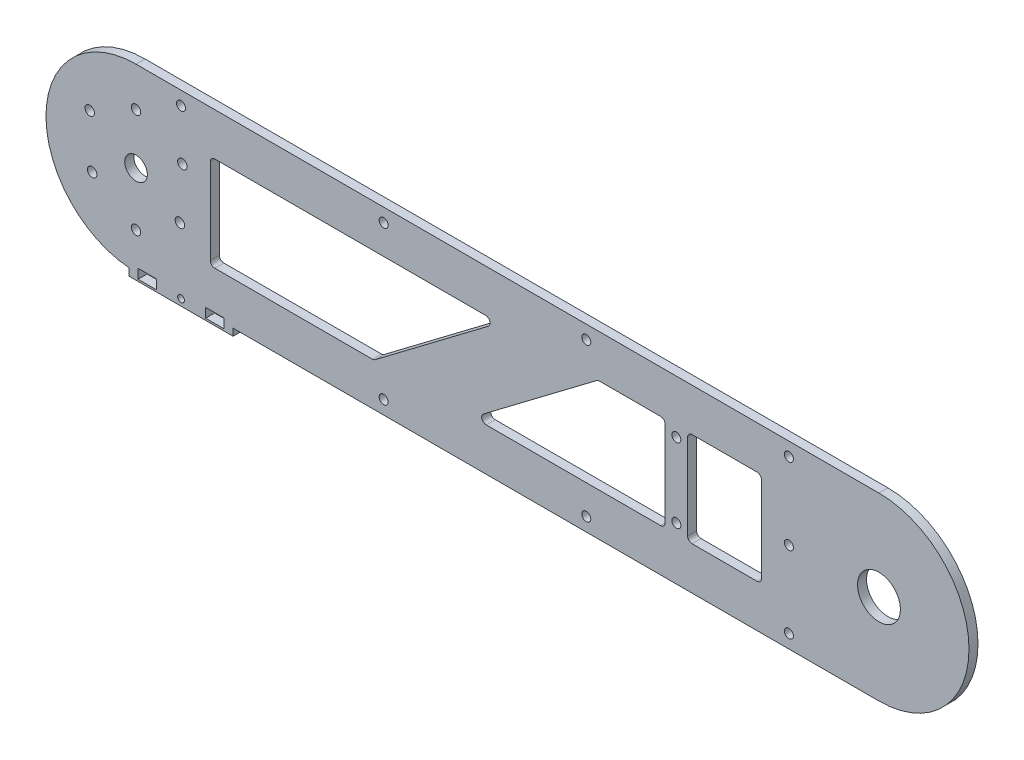
SolidWorks part; units mm, degrees
ref_plane "前视基准面" through (0, 0, 0) normal (0, 0, 1) x (1, 0, 0)
ref_plane "上视基准面" through (0, 0, 0) normal (0, 1, 0) x (1, 0, 0)
ref_plane "右视基准面" through (0, 0, 0) normal (1, 0, 0) x (0, 0, -1)
sketch "草图1" plane through (0, 0, 0) normal (0, 0, 1) x (1, 0, 0)
  line L0 (-1.4571, -0.1457) -> (37.8152, -22.8196) construction
  line L1 (-1.4571, -0.1457) -> (328.5429, -0.1457) construction
  line L3 (-1.4571, -40.1457) -> (328.5429, -40.1457)
  line L8 (-1.4571, 39.8543) -> (328.5429, 39.8543)
  circle A0 centre (-1.4571, -0.1457) radius 23.75 construction
  circle A1 centre (-1.4571, -0.1457) radius 22.5 construction
  circle A2 centre (-1.4571, -23.8957) radius 2.1
  circle A3 centre (18.0284, -11.3957) radius 2.1
  circle A4 centre (-1.4571, -0.1457) radius 40 construction
  circle A6 centre (-1.4571, -0.1457) radius 5.02
  circle A12 centre (328.5429, -0.1457) radius 40 construction
  arc A16 (-1.4571, -40.1457) -> (-1.4571, 39.8543) centre (-1.4571, -0.1457) cw
  arc A21 (328.5429, -40.1457) -> (328.5429, 39.8543) centre (328.5429, -0.1457) ccw
  circle A22 centre (328.5429, -0.1457) radius 9.52
  circle A23 centre (288.5429, -0.1457) radius 2
  circle A24 centre (238.5429, 16.3543) radius 2
  circle A25 centre (238.5429, -16.6457) radius 2
  circle A26 centre (-20.9427, -11.3957) radius 2.1
  circle A27 centre (-22.0252, 11.7293) radius 2.1
  circle A28 centre (-1.4571, 22.3543) radius 2.1
  circle A29 centre (19.111, 11.7293) radius 2.1
  dimension "D1" = 45
  dimension "D2" = 3
  dimension "D3" = 4.2
  dimension "D4" = 19.04
  dimension "D5" = 80
  dimension "D6" = 80
  dimension "D7" = 10.04
  dimension "D11" = 4
  dimension "D12" = 47.5
  dimension "D8" = 330
  dimension "D9" = 50
  dimension "D10" = 16.5
extrude "凸台-拉伸1" add sketch "草图1" along normal blind 4 contours L3
sketch "草图3" plane through (0, 0, 4) normal (0, 0, 1) x (1, 0, 0)
  line L1 (41.6429, -39.4527) -> (-4.5571, -39.4527)
  line L2 (41.6429, -39.4527) -> (41.6429, -43.2699)
  line L3 (41.6429, -43.2699) -> (-4.5571, -43.2699)
  line L4 (-4.5571, -39.4527) -> (-4.5571, -43.2699)
  line L7 (-1.4571, -40.1457) -> (328.5429, -40.1457) construction
  dimension "D1" = 3.1
  dimension "D2" = 46.2
  dimension "D3" = 3.1242
extrude "凸台-拉伸2" add sketch "草图3" against normal blind 4
sketch "草图2" plane through (0, 0, 4) normal (0, 0, 1) x (1, 0, 0)
  line L0 (18.5429, 33.8543) -> (198.5429, 33.8543) construction
  line L1 (108.5429, -34.1457) -> (198.5429, 33.8543) construction
  line L2 (18.5429, 33.8543) -> (18.5429, -34.1457) construction
  line L3 (18.5429, -34.1457) -> (108.5429, -34.1457) construction
  line L4 (31.5429, -21.1457) -> (104.1839, -21.1457)
  line L5 (104.1839, -21.1457) -> (159.7721, 20.8543)
  line L6 (31.5429, 20.8543) -> (159.7721, 20.8543)
  line L7 (31.5429, 20.8543) -> (31.5429, -21.1457)
  line L8 (108.5429, -34.1457) -> (288.5429, -34.1457) construction
  line L9 (288.5429, -34.1457) -> (288.5429, 33.8543) construction
  line L10 (288.5429, 33.8543) -> (198.5429, 33.8543) construction
  line L11 (276.3527, 20.8543) -> (203.7117, 20.8543) construction
  line L12 (148.1234, -21.1457) -> (203.7117, 20.8543)
  line L13 (148.1234, -21.1457) -> (276.3527, -21.1457) construction
  line L14 (276.3527, -21.1457) -> (276.3527, 20.8543)
  line L15 (233.5429, 20.8543) -> (233.5429, -21.1457)
  line L16 (243.5429, 20.8543) -> (243.5429, -21.1457)
  line L17 (238.5429, 16.3543) -> (238.5429, -16.6457) construction
  line L18 (233.5429, 20.8543) -> (203.7117, 20.8543)
  line L19 (243.5429, 20.8543) -> (276.3527, 20.8543)
  line L20 (243.5429, -21.1457) -> (276.3527, -21.1457)
  line L21 (233.5429, -21.1457) -> (148.1234, -21.1457)
  line L22 (41.6429, -40.1457) -> (328.5429, -40.1457) construction
  line L27 (18.5429, -34.1457) -> (18.5429, -40.1457) construction
  line L28 (41.6429, -40.1457) -> (328.5429, -40.1457) construction
  line L29 (29.4429, -38.2299) -> (37.6429, -38.2299)
  line L30 (29.4429, -38.2299) -> (29.4429, -42.4299)
  line L31 (29.4429, -42.4299) -> (37.6429, -42.4299)
  line L32 (37.6429, -38.2299) -> (37.6429, -42.4299)
  line L33 (29.4429, -38.2299) -> (37.6429, -42.4299) construction
  line L34 (29.4429, -42.4299) -> (37.6429, -38.2299) construction
  line L35 (-0.5571, -38.2299) -> (7.6429, -38.2299)
  line L36 (-0.5571, -38.2299) -> (-0.5571, -42.4299)
  line L37 (-0.5571, -42.4299) -> (7.6429, -42.4299)
  line L38 (7.6429, -38.2299) -> (7.6429, -42.4299)
  line L39 (-0.5571, -38.2299) -> (7.6429, -42.4299) construction
  line L40 (-0.5571, -42.4299) -> (7.6429, -38.2299) construction
  line L41 (-4.5571, -43.2699) -> (41.6429, -43.2699) construction
  circle A0 centre (18.5429, 33.8543) radius 2
  circle A1 centre (108.5429, 33.8543) radius 2
  circle A2 centre (198.5429, 33.8543) radius 2
  circle A3 centre (288.5429, 33.8543) radius 2
  circle A4 centre (108.5429, -34.1457) radius 2
  circle A5 centre (198.5429, -34.1457) radius 2
  circle A6 centre (288.5429, -34.1457) radius 2
  arc A8 (-1.4571, 39.8543) -> (-4.5571, -40.0254) centre (-1.4571, -0.1457) ccw construction
  circle A9 centre (18.5429, -40.3299) radius 1.5
  point P2 (-1.4571, -0.1457)
  point P40 (33.5429, -40.3299)
  point P46 (3.5429, -40.3299)
  dimension "D1" = 4
  dimension "D6" = 15
  dimension "D12" = 3
  dimension "D14" = 68
  dimension "D2" = 34
  dimension "D3" = 20
  dimension "D4" = 10
  dimension "D5" = 20
  dimension "D7" = 8.2
  dimension "D8" = 4.2
  dimension "D9" = 15
  dimension "D10" = 8.2
  dimension "D11" = 4.2
  dimension "D13" = 6
  dimension "D15" = 2.94
extrude "切除-拉伸1" cut sketch "草图2" against normal blind 4
fillet "圆角1" radius 2 12 edges at (243.5429, -21.1457, 2) (243.5429, 20.8543, 2) (276.3527, -21.1457, 2) (276.3527, 20.8543, 2) (233.5429, -21.1457, 2) (233.5429, 20.8543, 2) (203.7117, 20.8543, 2) (148.1234, -21.1457, 2) (159.7721, 20.8543, 2) (104.1839, -21.1457, 2) (31.5429, -21.1457, 2) (31.5429, 20.8543, 2)
